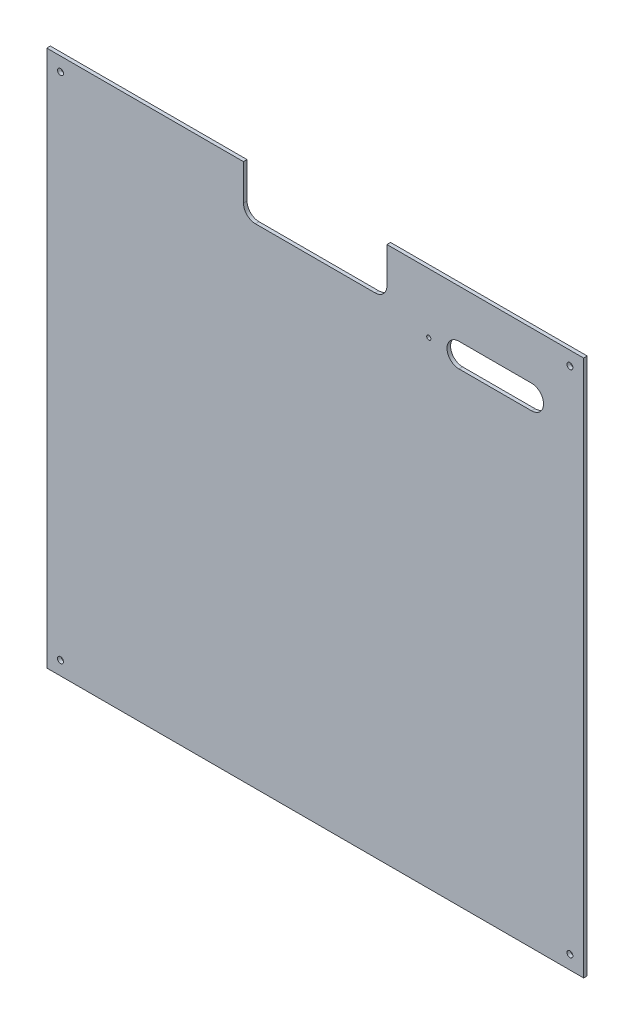
SolidWorks part; units mm, degrees
ref_plane "Piano frontale" through (0, 0, 0) normal (0, 0, 1) x (1, 0, 0)
ref_plane "Piano superiore" through (0, 0, 0) normal (0, 1, 0) x (1, 0, 0)
ref_plane "Piano destro" through (0, 0, 0) normal (1, 0, 0) x (0, 0, -1)
sketch "Schizzo1" plane through (0, 0, 0) normal (0, 0, 1) x (1, 0, 0)
  line L0 (0, 0) -> (0, 449)
  line L1 (0, 449) -> (164.5, 449)
  line L2 (449, 449) -> (449, 0)
  line L3 (449, 0) -> (0, 0)
  line L4 (164.5, 449) -> (164.5, 419)
  line L5 (174.5, 409) -> (274.5, 409)
  line L6 (284.5, 419) -> (284.5, 449)
  line L7 (284.5, 449) -> (449, 449)
  line L8 (154.5, 399) -> (294.5, 399) construction
  line L9 (224.5, 379) -> (224.5, 419) construction
  line L10 (344.7159, 399) -> (405.4404, 399) construction
  line L11 (344.7159, 409) -> (405.4404, 409)
  line L12 (344.7159, 389) -> (405.4404, 389)
  line L13 (0, 224.5) -> (449, 224.5) construction
  line L23 (73.9219, 399) -> (73.9219, 449) construction
  line L24 (164.5, 434) -> (304.5, 434) construction
  arc A0 (164.5, 419) -> (174.5, 409) centre (174.5, 419) ccw
  arc A1 (284.5, 419) -> (274.5, 409) centre (274.5, 419) cw
  circle A2 centre (11.5, 11.5) radius 2.5
  circle A3 centre (437.5, 11.5) radius 2.5
  circle A4 centre (437.5, 437.5) radius 2.5
  circle A5 centre (11.5, 437.5) radius 2.5
  circle A6 centre (319.5, 399) radius 1.75
  arc A8 (344.7159, 409) -> (344.7159, 389) centre (344.7159, 399) ccw
  arc A9 (405.4404, 389) -> (405.4404, 409) centre (405.4404, 399) ccw
  point P11 (164.5, 409)
  point P14 (284.5, 409)
  point P33 (375.0781, 399)
  dimension "D5" = 10
  dimension "D6" = 11.5
  dimension "D7" = 11.5
  dimension "D8" = 5
  dimension "D9" = 3.5
  dimension "D10" = 35
  dimension "D1" = 449
  dimension "D2" = 449
  dimension "D3" = 120
  dimension "D4" = 40
  dimension "D11" = 20
  dimension "D21" = 50
extrude "Estrusione-Estrusione1" add sketch "Schizzo1" along normal blind 3
